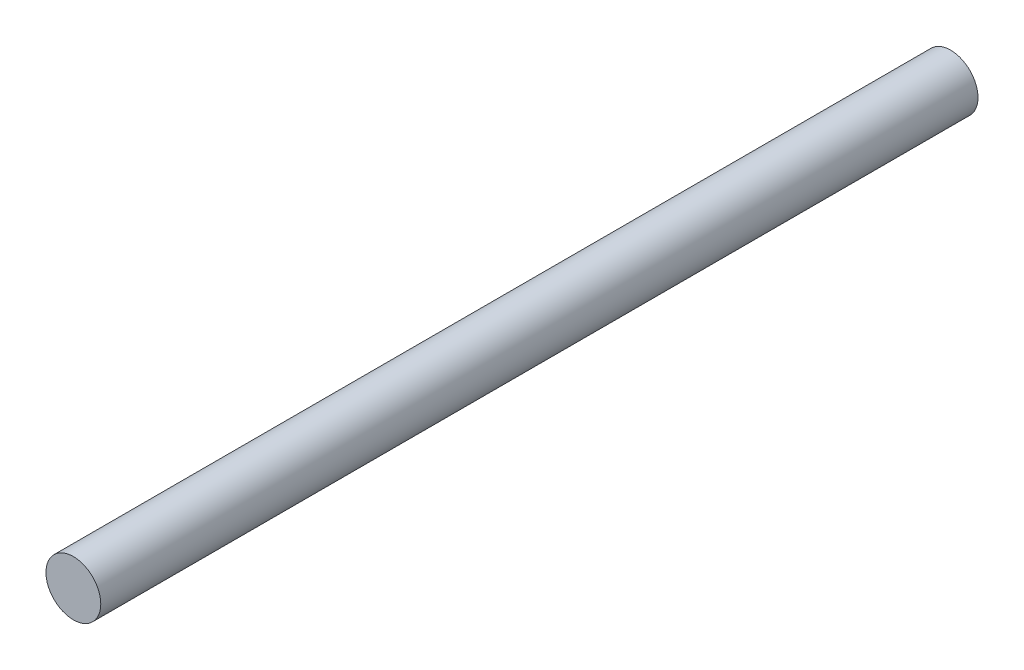
SolidWorks part; units mm, degrees
material "AISI 1020"
ref_plane "Plan de face" through (0, 0, 0) normal (0, 0, 1) x (1, 0, 0)
ref_plane "Plan de dessus" through (0, 0, 0) normal (0, 1, 0) x (1, 0, 0)
ref_plane "Plan de droite" through (0, 0, 0) normal (1, 0, 0) x (0, 0, -1)
sketch "Esquisse1" plane through (0, 0, 0) normal (0, 0, 1) x (1, 0, 0)
  circle A0 centre (0, 0) radius 12.5
  dimension "D1" = 25
extrude "Boss.-Extru.1" add sketch "Esquisse1" along normal blind 400
